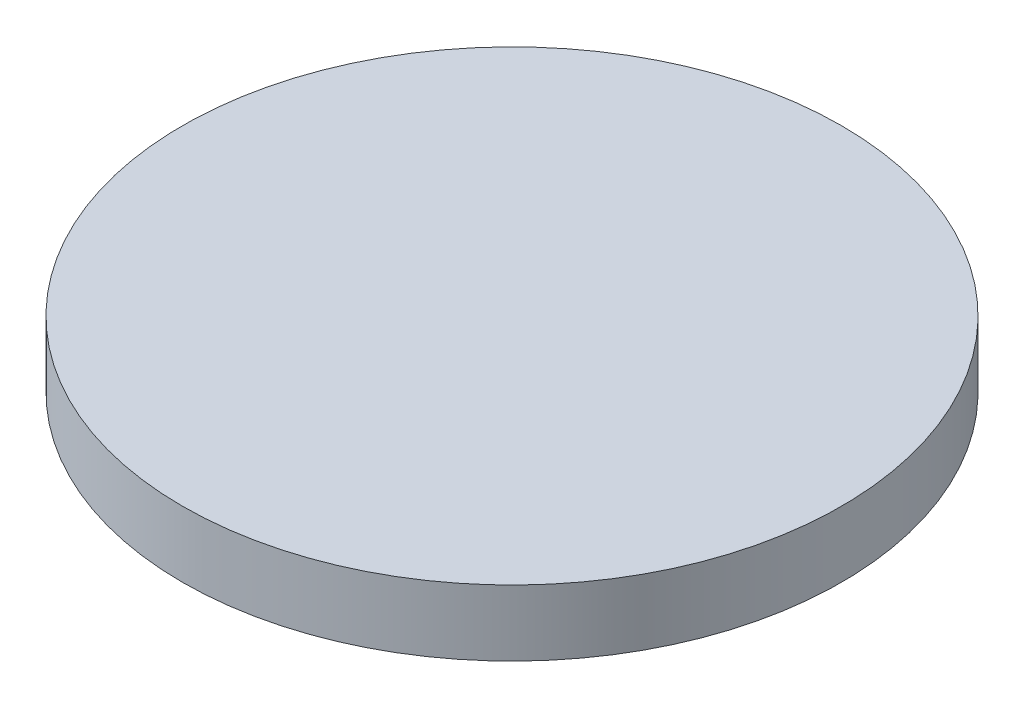
SolidWorks part; units mm, degrees
material "Natural Rubber"
ref_plane "Front Plane" through (0, 0, 0) normal (0, 0, 1) x (1, 0, 0)
ref_plane "Top Plane" through (0, 0, 0) normal (0, 1, 0) x (1, 0, 0)
ref_plane "Right Plane" through (0, 0, 0) normal (1, 0, 0) x (0, 0, -1)
sketch "BaseS" plane through (0, 0, 0) normal (0, 1, 0) x (1, 0, 0)
  circle A0 centre (0, 0) radius 2.5
  dimension "Dia" = 5
extrude "BASE" add sketch "BaseS" against normal blind 0.5
